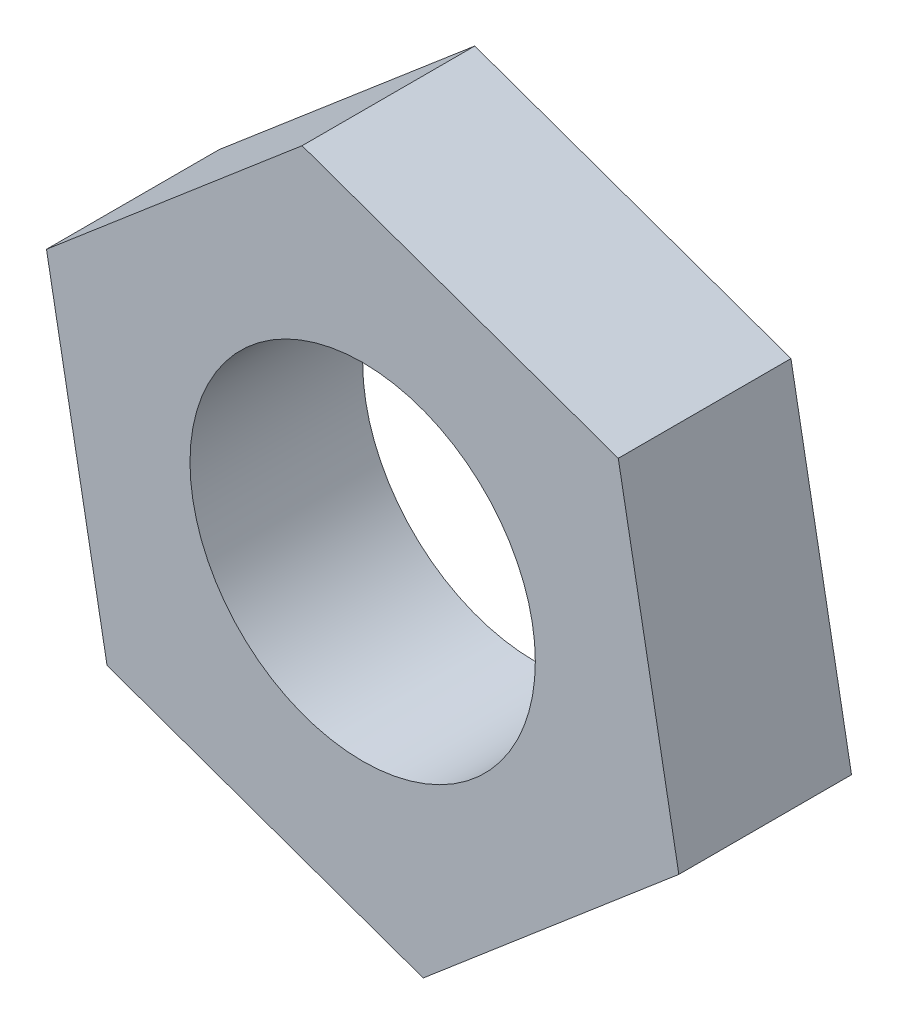
SolidWorks part; units mm, degrees
ref_plane "Front Plane" through (0, 0, 0) normal (0, 0, 1) x (1, 0, 0)
ref_plane "Top Plane" through (0, 0, 0) normal (0, 1, 0) x (1, 0, 0)
ref_plane "Right Plane" through (0, 0, 0) normal (1, 0, 0) x (0, 0, -1)
sketch "Sketch1" plane through (0, 0, 0) normal (0, 0, 1) x (1, 0, 0)
  line L1 (1324.4991, -1696.9218) -> (1328.9401, -1693.1429)
  line L2 (1328.9401, -1693.1429) -> (1327.8881, -1687.4074)
  line L3 (1327.8881, -1687.4074) -> (1322.3949, -1685.4507)
  line L4 (1322.3949, -1685.4507) -> (1317.9538, -1689.2296)
  line L5 (1317.9538, -1689.2296) -> (1319.0059, -1694.9652)
  line L6 (1324.1558, -1686.1863) -> (1322.7382, -1686.1863)
  line L7 (1319.4713, -1688.0724) -> (1318.7625, -1689.3001)
  line L8 (1318.7625, -1693.0724) -> (1319.4713, -1694.3001)
  line L9 (1322.7382, -1696.1863) -> (1324.1558, -1696.1863)
  line L10 (1327.4227, -1694.3001) -> (1328.1315, -1693.0724)
  line L11 (1328.1315, -1689.3001) -> (1327.4227, -1688.0724)
  line L12 (1324.1558, -1686.1863) -> (1322.7382, -1686.1863)
  line L13 (1319.4713, -1688.0724) -> (1318.7625, -1689.3001)
  line L14 (1318.7625, -1693.0724) -> (1319.4713, -1694.3001)
  line L15 (1322.7382, -1696.1863) -> (1324.1558, -1696.1863)
  line L16 (1327.4227, -1694.3001) -> (1328.1315, -1693.0724)
  line L17 (1328.1315, -1689.3001) -> (1327.4227, -1688.0724)
  line L18 (1319.0059, -1694.9652) -> (1324.4991, -1696.9218)
  arc A0 (1327.4227, -1688.0724) -> (1324.1558, -1686.1863) centre (1323.447, -1691.1863) ccw
  arc A1 (1322.7382, -1686.1863) -> (1319.4713, -1688.0724) centre (1323.447, -1691.1863) ccw
  arc A2 (1318.7625, -1689.3001) -> (1318.7625, -1693.0724) centre (1323.447, -1691.1863) ccw
  arc A3 (1319.4713, -1694.3001) -> (1322.7382, -1696.1863) centre (1323.447, -1691.1863) ccw
  arc A4 (1324.1558, -1696.1863) -> (1327.4227, -1694.3001) centre (1323.447, -1691.1863) ccw
  arc A5 (1328.1315, -1693.0724) -> (1328.1315, -1689.3001) centre (1323.447, -1691.1863) ccw
  arc A6 (1327.4227, -1688.0724) -> (1324.1558, -1686.1863) centre (1323.447, -1691.1863) ccw
  arc A7 (1322.7382, -1686.1863) -> (1319.4713, -1688.0724) centre (1323.447, -1691.1863) ccw
  arc A8 (1318.7625, -1689.3001) -> (1318.7625, -1693.0724) centre (1323.447, -1691.1863) ccw
  arc A9 (1319.4713, -1694.3001) -> (1322.7382, -1696.1863) centre (1323.447, -1691.1863) ccw
  arc A10 (1324.1558, -1696.1863) -> (1327.4227, -1694.3001) centre (1323.447, -1691.1863) ccw
  arc A11 (1328.1315, -1693.0724) -> (1328.1315, -1689.3001) centre (1323.447, -1691.1863) ccw
  circle A12 centre (1323.447, -1691.1863) radius 5.05 construction
  circle A13 centre (1323.447, -1691.1863) radius 3
  dimension "D2" = 6
  dimension "D1" = 0
extrude "Boss-Extrude1" add sketch "Sketch1" along normal blind 3 contours A11 L17 A6 L12 A7 L13 A8 L14 A9 L15 A10 L16 A13 | A10 L15 A9 L18 L1 | A11 L16 A10 L1 L2 | A11 L2 L3 A6 L17 | A7 L12 A6 L3 L4 | A8 L13 A7 L4 L5 | A9 L14 A8 L5 L18
